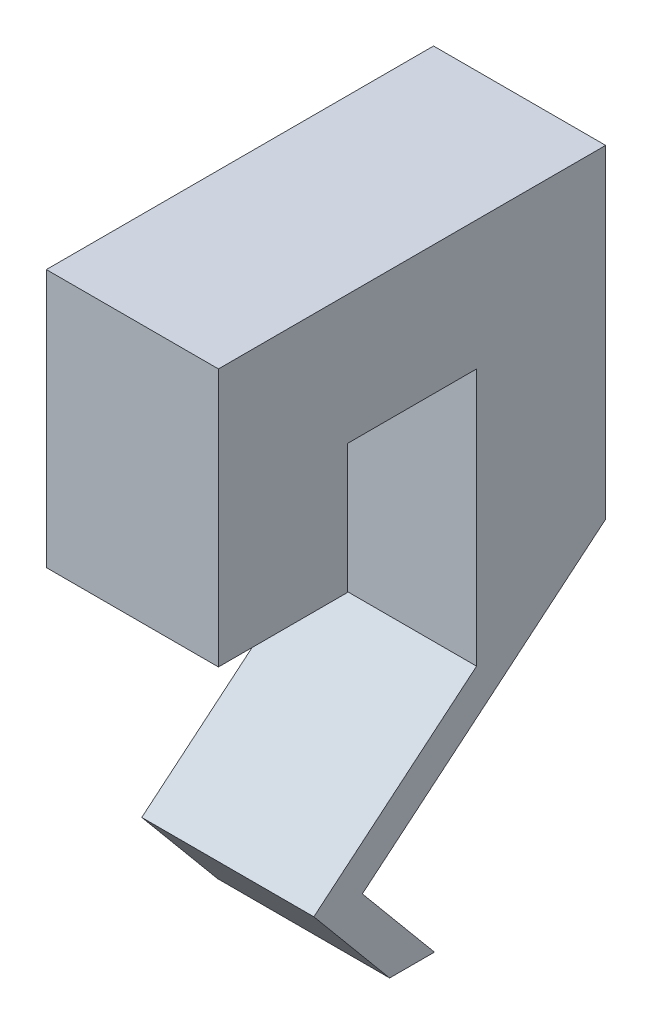
SolidWorks part; units mm, degrees
ref_plane "前视基准面" through (0, 0, 0) normal (0, 0, 1) x (1, 0, 0)
ref_plane "上视基准面" through (0, 0, 0) normal (0, 1, 0) x (1, 0, 0)
ref_plane "右视基准面" through (0, 0, 0) normal (1, 0, 0) x (0, 0, -1)
sketch "Sketch1" plane through (0, 0, 0) normal (1, 0, 0) x (0, 0, -1)
  line L0 (0, 0) -> (3, 0)
  line L1 (3, 0) -> (3, -5.9836)
  line L2 (3, -5.9836) -> (-0.7824, -9.137)
  line L3 (0, 0) -> (0, -3)
  line L4 (0, -3) -> (-3, -3)
  line L5 (-3, -3) -> (-3, 3)
  line L6 (-3, 3) -> (6, 3)
  line L7 (6, 3) -> (6, -4.5241)
  line L8 (6, -4.5241) -> (0.3444, -9.2392)
  line L9 (1.5, 0) -> (1.5, -11.25) construction
  line L10 (-0.7824, -9.137) -> (0.9792, -11.25)
  line L11 (0.9792, -11.25) -> (2.0208, -11.25)
  line L14 (0, 0) -> (0, 3) construction
  line L15 (2.0208, -11.25) -> (0.3444, -9.2392)
  dimension "D1" = 3
  dimension "D2" = 0.8
  dimension "D3" = 3
  dimension "D4" = 11.25
  dimension "D5" = 0.8
extrude "Boss-Extrude1" add sketch "Sketch1" along normal blind 4
